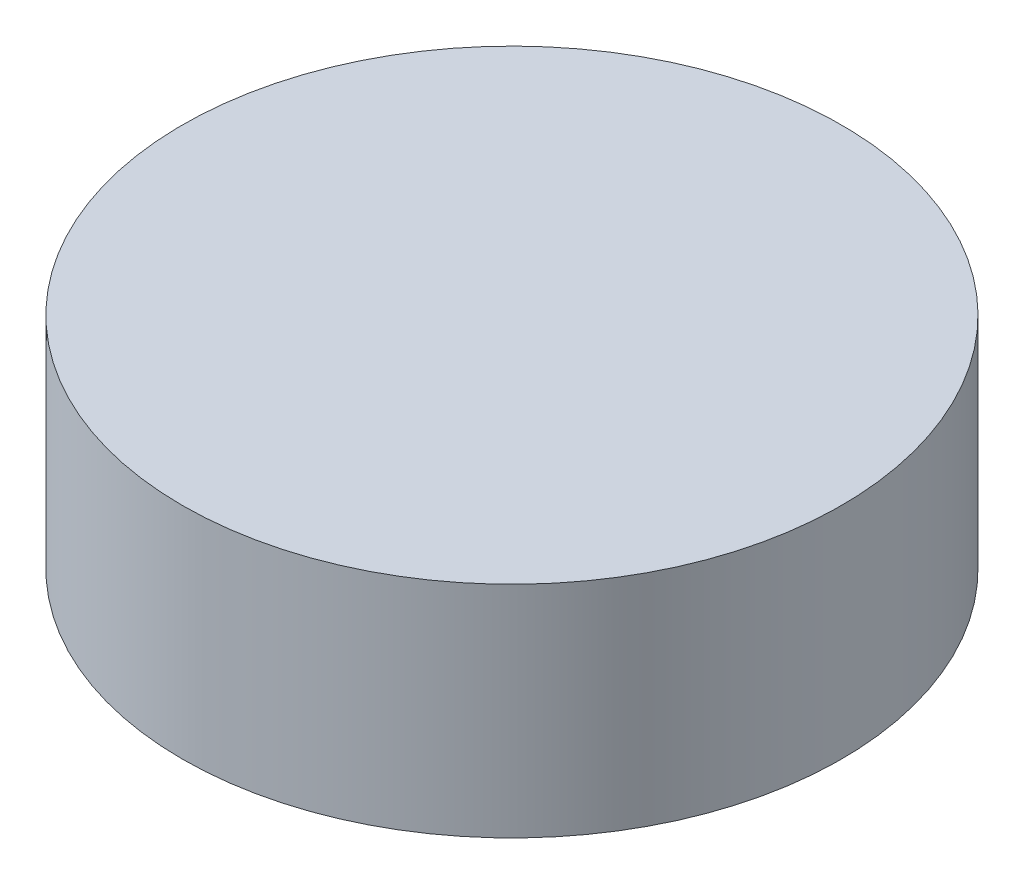
SolidWorks part; units mm, degrees
ref_plane "Front Plane" through (0, 0, 0) normal (0, 0, 1) x (1, 0, 0)
ref_plane "Top Plane" through (0, 0, 0) normal (0, 1, 0) x (1, 0, 0)
ref_plane "Right Plane" through (0, 0, 0) normal (1, 0, 0) x (0, 0, -1)
sketch "Sketch1" plane through (0, 0, 0) normal (0, 1, 0) x (1, 0, 0)
  circle A0 centre (0, 0) radius 30
  dimension "D1" = 60
extrude "Boss-Extrude1" add sketch "Sketch1" along normal mid plane 20
sketch "Sketch2" plane through (0, -10, 0) normal (0, -1, 0) x (1, 0, 0)
  circle A0 centre (0, 0) radius 19
  circle A1 centre (0, 0) radius 30 construction
  dimension "D1" = 11
extrude "Cut-Extrude1" cut sketch "Sketch2" against normal blind 15
